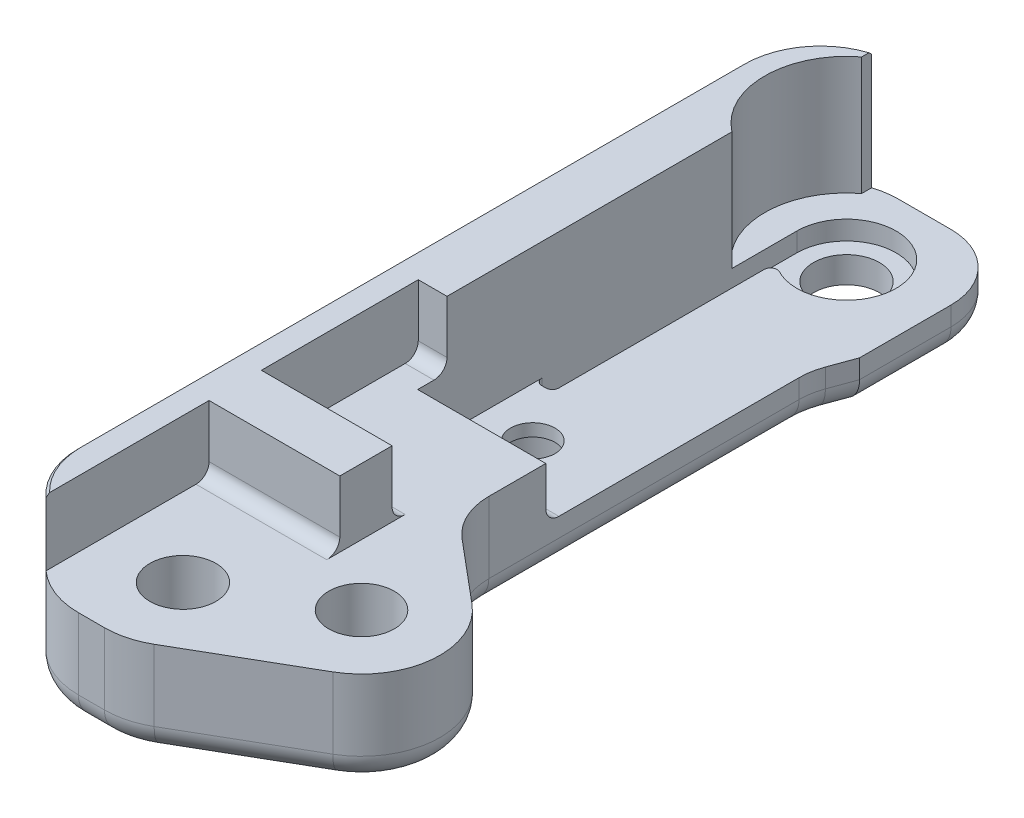
SolidWorks part; units mm, degrees
ref_plane "前视基准面" through (0, 0, 0) normal (0, 0, 1) x (1, 0, 0)
ref_plane "上视基准面" through (0, 0, 0) normal (0, 1, 0) x (1, 0, 0)
ref_plane "右视基准面" through (0, 0, 0) normal (1, 0, 0) x (0, 0, -1)
other "Configuration Table"
ref_plane "基准面1" through (0, 7.45, 0) normal (0, 1, 0) x (1, 0, 0)
sketch "草图1" plane through (0, 7.45, 0) normal (0, 1, 0) x (1, 0, 0)
  line L0 (6, 15.0647) -> (6, 56.7543)
  line L1 (6, 56.7543) -> (-8, 56.7543)
  line L2 (-8, 56.7543) -> (-8, -6)
  line L3 (-8, -6) -> (1.6077, -6)
  line L4 (1.6077, -6) -> (11.6603, -0.1962)
  line L5 (12.517, 9.5963) -> (6, 15.0647)
  arc A0 (11.6603, -0.1962) -> (12.517, 9.5963) centre (8.6603, 5) ccw
  dimension "D1" = 6
  dimension "D2" = 9.6077
  dimension "D3" = 14
  dimension "D4" = 16.6603
  dimension "D5" = 19.6603
  dimension "D6" = 20.517
  dimension "D7" = 62.7543
extrude "凸台-拉伸1" add sketch "草图1" against normal blind 7.45
ref_plane "基准面2" through (0, 0, 0) normal (0, -1, 0) x (1, 0, 0)
sketch "草图2" plane through (0, 0, 0) normal (0, -1, 0) x (1, 0, 0)
  line L0 (6, -42.0068) -> (6, -56.7543)
  line L1 (6, -56.7543) -> (7, -56.7543)
  line L2 (7, -56.7543) -> (7, -44.7543)
  line L3 (7, -44.7543) -> (6, -42.0068)
  dimension "D1" = 1
  dimension "D2" = 12
  dimension "D3" = 14.7475
extrude "凸台-拉伸2" add sketch "草图2" against normal blind 3.45
sketch "草图3" plane through (6, 0, 0) normal (1, 0, 0) x (0, 0, -1)
  line L0 (56.7543, 3.45) -> (56.7543, 7.45)
  line L1 (56.7543, 7.45) -> (30.7543, 7.45)
  line L2 (30.7543, 7.45) -> (30.7543, 3.45)
  line L3 (30.7543, 3.45) -> (56.7543, 3.45)
  line L4 (42.0068, 3.45) -> (56.7543, 3.45) construction
  dimension "D1" = 26
  dimension "D2" = 4
extrude "切除-拉伸1" cut sketch "草图3" against normal blind 9.8
sketch "草图4" plane through (0, 7.45, 0) normal (0, 1, 0) x (-1, 0, 0)
  line L0 (3.8, 6) -> (8, 6)
  line L1 (8, 6) -> (8, -56.7543)
  line L2 (8, -56.7543) -> (3.8, -56.7543)
  line L3 (3.8, -56.7543) -> (3.8, 6)
  line L4 (8, -56.7543) -> (8, 6) construction
  dimension "D1" = 4.2
  dimension "D2" = 62.7543
extrude "凸台-拉伸3" add sketch "草图4" along normal blind 5.05
sketch "草图5" plane through (0, 3.45, 0) normal (0, 1, 0) x (-1, 0, 0)
  line L0 (3.8, -30.7543) -> (2.5, -30.7543)
  line L1 (2.5, -30.7543) -> (2.5, -46.9477)
  line L2 (3.8, -50.7543) -> (3.8, -30.7543)
  line L3 (-7, -56.7543) -> (-7, -44.7543) construction
  arc A0 (2.5, -46.9477) -> (1.7674, -47.3904) centre (2, -46.9477) cw
  arc A1 (1.7674, -47.3904) -> (3.8, -50.7543) centre (0, -50.7543) ccw
  dimension "D1" = 0.5
  dimension "D2" = 3.8
  dimension "D3" = 7
  dimension "D4" = 8.7674
  dimension "D5" = 6
  dimension "D8" = 26
extrude "切除-拉伸2" cut sketch "草图5" against normal blind 1.45
sketch "草图6" plane through (0, 7.45, 0) normal (0, 1, 0) x (-1, 0, 0)
  line L0 (3.8, -12) -> (-4, -12)
  line L1 (-4, -12) -> (-4, -8)
  line L2 (-4, -8) -> (3.8, -8)
  line L3 (3.8, -8) -> (3.8, -12)
  line L4 (3.8, 6) -> (3.8, -30.7543) construction
  dimension "D1" = 7.8
  dimension "D2" = 1.5963
  dimension "D3" = 2.4037
extrude "凸台-拉伸4" add sketch "草图6" along normal blind 5.05
sketch "草图7" plane through (0, 0, -30.7543) normal (0, 0, -1) x (-1, 0, 0)
  line L0 (-6, 7.45) -> (-6, 3.45)
  line L1 (-6, 3.45) -> (3.8, 3.45)
  line L2 (3.8, 3.45) -> (3.8, 7.45)
  line L3 (3.8, 7.45) -> (-6, 7.45)
  line L4 (2.5, 2) -> (2.5, 3.45) construction
  line L5 (2.5, 3.45) -> (-6, 3.45) construction
  dimension "D1" = 1.3
  dimension "D2" = 8.5
  dimension "D3" = 4
extrude "切除-拉伸3" cut sketch "草图7" against normal blind 9
sketch "草图8" plane through (0, 12.5, 0) normal (0, 1, 0) x (-1, 0, 0)
  line L0 (3.8, -45.7922) -> (3.8, -55.7164)
  line L1 (3.8, 6) -> (3.8, -8) construction
  arc A0 (3.8, -55.7164) -> (3.8, -45.7922) centre (0, -50.7543) ccw
  dimension "D1" = 6.25
  dimension "D2" = 3.8
  dimension "D3" = 51.7922
  dimension "D4" = 56.7543
extrude "切除-拉伸4" cut sketch "草图8" against normal blind 9.05
ref_plane "基准面3" through (-3.8, 0, 0) normal (1, 0, 0) x (0, 0, -1)
ref_plane "基准面4" through (-6, 0, 0) normal (-1, 0, 0) x (0, -1, 0)
sketch "草图10" plane through (-6, 0, 0) normal (-1, 0, 0) x (0, -1, 0)
  line L0 (-12.5, -24) -> (-7.45, -24)
  line L1 (-7.45, -24) -> (-7.45, -12)
  line L2 (-7.45, -12) -> (-12.5, -12)
  line L3 (-12.5, -12) -> (-12.5, -24)
  dimension "D1" = 5.05
  dimension "D2" = 12
extrude "切除-拉伸5" cut sketch "草图10" against normal up to surface up to plane "基准面3"
sketch "草图11" plane through (-3.8, 0, 0) normal (1, 0, 0) x (0, 0, -1)
  line L0 (8, 12.5) -> (-6, 12.5)
  line L1 (-6, 12.5) -> (-6, 7.45)
  line L2 (-6, 7.45) -> (8, 7.45)
  line L3 (8, 7.45) -> (8, 12.5)
  line L4 (-6, 7.45) -> (8, 7.45) construction
  dimension "D1" = 14
  dimension "D2" = 5.05
extrude "切除-拉伸6" cut sketch "草图11" against normal blind 2.2
hole_wizard "孔1" positions "草图13" profile "草图12" legacy
sketch "草图13" plane through (0, 7.45, 0) normal (0, 1, 0) x (1, 0, 0)
  point P0 (8.6603, 5)
sketch "草图12" plane through (8.6603, 7.45, -5) normal (1, 0, 0) x (0, 0, 1)
  line L0 (0, 0) -> (0, 7.45)
  line L1 (0, 7.45) -> (2.505, 7.45)
  line L2 (2.505, 7.45) -> (2.505, 0)
  line L3 (2.505, 0) -> (0, 0)
  line L4 (0, 110) -> (0, -10) construction
  dimension "直径" = 5.01
  dimension "深度" = 7.45
hole_wizard "孔2" positions "草图15" profile "草图14" legacy
sketch "草图15" plane through (0, 7.45, 0) normal (0, 1, 0) x (1, 0, 0)
  point P0 (0, 0)
sketch "草图14" plane through (0, 7.45, 0) normal (1, 0, 0) x (0, 0, 1)
  line L0 (0, 0) -> (0, 7.45)
  line L1 (0, 7.45) -> (2.525, 7.45)
  line L2 (2.525, 7.45) -> (2.525, 0)
  line L3 (2.525, 0) -> (0, 0)
  line L4 (0, 110) -> (0, -10) construction
  dimension "直径" = 5.05
  dimension "深度" = 7.45
hole_wizard "孔3" positions "草图17" profile "草图16" legacy
sketch "草图17" plane through (0, 2, 0) normal (0, 1, 0) x (1, 0, 0)
  point P0 (0, 50.7543)
sketch "草图16" plane through (0, 2, -50.7543) normal (1, 0, 0) x (0, 0, 1)
  line L0 (0, 0) -> (0, 2)
  line L1 (0, 2) -> (2.525, 2)
  line L2 (2.525, 2) -> (2.525, 0)
  line L3 (2.525, 0) -> (0, 0)
  line L4 (0, 110) -> (0, -10) construction
  dimension "直径" = 5.05
  dimension "深度" = 2
hole_wizard "孔4" positions "草图19" profile "草图18" legacy
sketch "草图19" plane through (0, 0, 0) normal (0, -1, 0) x (-1, 0, 0)
  point P0 (0, 26.7543)
sketch "草图18" plane through (0, 0, -26.7543) normal (1, 0, 0) x (0, 0, -1)
  line L0 (0, 0) -> (0, 12.5)
  line L1 (0, 12.5) -> (1.7, 12.5)
  line L2 (1.7, 12.5) -> (1.7, 2.5)
  line L3 (1.7, 2.5) -> (3, 2.5)
  line L4 (3, 2.5) -> (3, 0)
  line L5 (3, 0) -> (0, 0)
  line L6 (0, 110) -> (0, -10) construction
  dimension "直径" = 3.4
  dimension "深度" = 12.5
  dimension "柱坑直径" = 6
  dimension "柱坑深度" = 2.5
fillet "圆角1" radius 5 3 edges at (6, 1.725, -42.0068) (7, 1.725, -56.7543) (6, 3.725, -15.0647)
fillet "圆角2" radius 6 3 edges at (-8, 6.25, -56.7543) (-8, 6.25, 6) (1.6077, 3.725, 6)
chamfer "倒角1" distance 0.2 angle 45 3 edges at (-7.4772, 12.5, 2.4495) (-8, 12.5, -25.3772) (-6.8374, 12.5, -54.304)
fillet "圆角3" radius 0.5 2 edges at (-2.5, 2.725, -30.7543) (-3.8, 2.725, -30.7543)
fillet "圆角4" radius 1 4 edges at (-1, 7.45, -8) (-4.9, 7.45, -24) (1.1, 3.45, -21.7543) (-1, 7.45, -12)
fillet "圆角5" radius 2 15 edges at (7, 0, -48.2543) (6.6508, 0, -43.7948) (5.5355, 0, -55.2898) (6.076, 0, -41.9934) (0, 0, -56.7543) (6, 0, -29.2607) (-6.2426, 0, -54.997) (6.4685, 0, -15.2831) (-8, 0, -25.3772) (10.1515, 0, -11.5811) (-6.2426, 0, 4.2426) (14.6374, 0, -4.4771) (-1, 0, 6) (7.3301, 0, 2.6962) (1.5529, 0, 5.7956)
